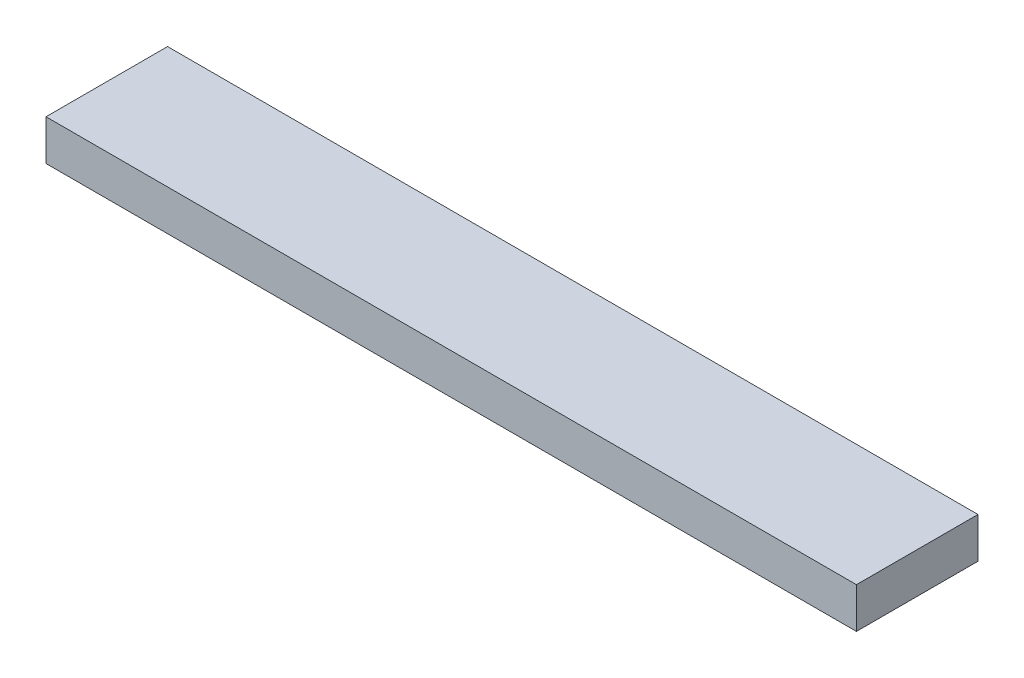
SolidWorks part; units mm, degrees
ref_plane "Alzado" through (0, 0, 0) normal (0, 0, 1) x (1, 0, 0)
ref_plane "Planta" through (0, 0, 0) normal (0, 1, 0) x (1, 0, 0)
ref_plane "Vista lateral" through (0, 0, 0) normal (1, 0, 0) x (0, 0, -1)
sketch "Croquis2" plane through (0, 0, 0) normal (0, 1, 0) x (1, 0, 0)
  line L1 (-500, -75) -> (500, -75)
  line L2 (-500, -75) -> (-500, 75)
  line L3 (-500, 75) -> (500, 75)
  line L4 (500, -75) -> (500, 75)
  line L5 (-500, -75) -> (500, 75) construction
  line L6 (-500, 75) -> (500, -75) construction
  point P0 (0, 0)
  dimension "D1" = 1000
  dimension "D2" = 150
extrude "Saliente-Extruir1" add sketch "Croquis2" along normal blind 50
